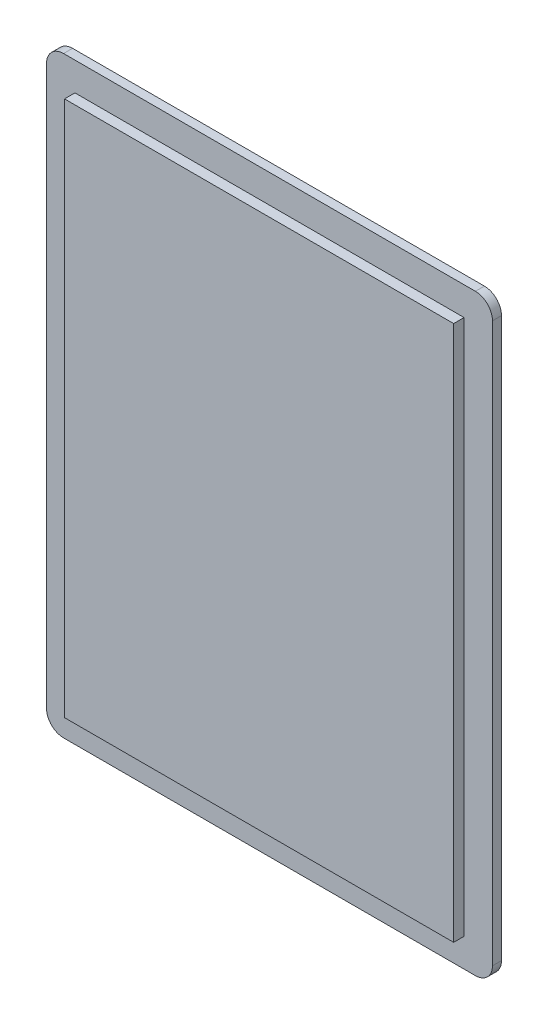
SolidWorks part; units mm, degrees
material "Стекло"
ref_plane "Спереди" through (0, 0, 0) normal (0, 0, 1) x (1, 0, 0)
ref_plane "Сверху" through (0, 0, 0) normal (0, 1, 0) x (1, 0, 0)
ref_plane "Справа" through (0, 0, 0) normal (1, 0, 0) x (0, 0, -1)
other "Configuration Table"
sketch "Эскиз1" plane through (0, 0, 0) normal (0, 0, 1) x (1, 0, 0)
  line L1 (-235.5, -313) -> (235.5, -313)
  line L2 (-235.5, -313) -> (-235.5, 313)
  line L3 (-235.5, 313) -> (235.5, 313)
  line L4 (235.5, -313) -> (235.5, 313)
  line L5 (-235.5, -313) -> (235.5, 313) construction
  line L6 (-235.5, 313) -> (235.5, -313) construction
  point P0 (0, 0)
  dimension "D1" = 471
  dimension "D2" = 626
extrude "Бобышка-Вытянуть1" add sketch "Эскиз1" along normal mid plane 9.5
fillet "Скругление1" radius 18 4 edges at (-235.5, -313, 0) (235.5, -313, 0) (235.5, 313, 0) (-235.5, 313, 0)
sketch "Эскиз2" plane through (0, 0, 4.75) normal (0, 0, 1) x (1, 0, 0)
  line L8 (-205.5, 283) -> (-205.5, -283)
  line L9 (-205.5, -283) -> (205.5, -283)
  line L10 (205.5, -283) -> (205.5, 283)
  line L11 (205.5, 283) -> (-205.5, 283)
  line L12 (-205.5, 283) -> (-205.5, -283)
  line L13 (-205.5, -283) -> (205.5, -283)
  line L14 (205.5, -283) -> (205.5, 283)
  line L15 (205.5, 283) -> (-205.5, 283)
  dimension "D1" = 30
extrude "Бобышка-Вытянуть2" add sketch "Эскиз2" along normal blind 11
